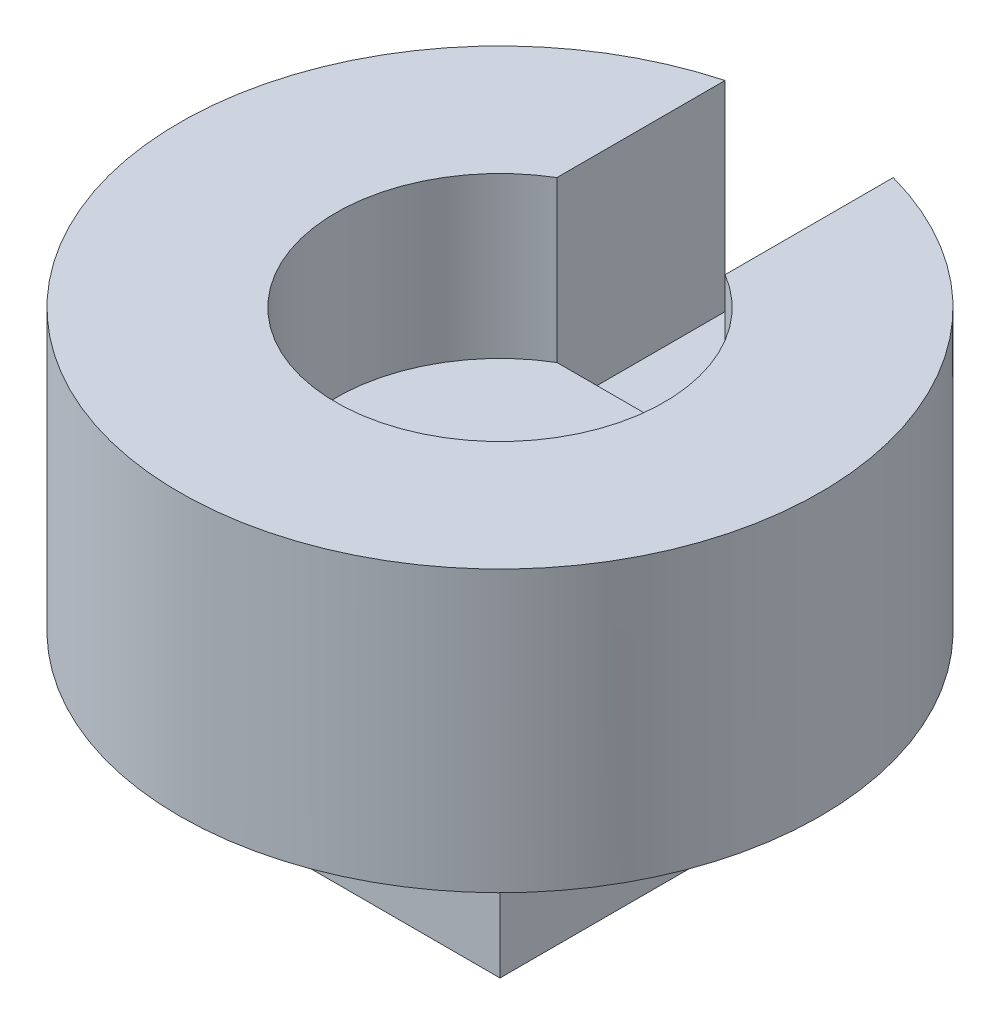
SolidWorks part; units mm, degrees
ref_plane "Front Plane" through (0, 0, 0) normal (0, 0, 1) x (1, 0, 0)
ref_plane "Top Plane" through (0, 0, 0) normal (0, 1, 0) x (1, 0, 0)
ref_plane "Right Plane" through (0, 0, 0) normal (1, 0, 0) x (0, 0, -1)
sketch "Sketch1" plane through (0, 0, 0) normal (0, 1, 0) x (1, 0, 0)
  line L1 (-1.25, -1.25) -> (1.25, -1.25)
  line L2 (-1.25, -1.25) -> (-1.25, 1.25)
  line L3 (-1.25, 1.25) -> (1.25, 1.25)
  line L4 (1.25, -1.25) -> (1.25, 1.25)
  line L5 (-1.25, -1.25) -> (1.25, 1.25) construction
  line L6 (-1.25, 1.25) -> (1.25, -1.25) construction
  point P0 (0, 0)
  dimension "D1" = 2.5
extrude "Boss-Extrude1" add sketch "Sketch1" along normal blind 2.5
sketch "Sketch2" plane through (0, 2.5, 0) normal (0, 1, 0) x (1, 0, 0)
  circle A0 centre (0, 0) radius 4
  dimension "D1" = 8
extrude "Boss-Extrude2" add sketch "Sketch2" along normal blind 3.5
sketch "Sketch3" plane through (0, 6, 0) normal (0, 1, 0) x (1, 0, 0)
  line L2 (-1.05, 1.7607) -> (1.05, 1.7607)
  line L3 (-1.05, 1.7607) -> (-1.05, 4)
  line L4 (-1.05, 4) -> (1.05, 4)
  line L5 (1.05, 1.7607) -> (1.05, 4)
  circle A0 centre (0, 0) radius 2.05
  circle A1 centre (0, 0) radius 4 construction
  circle M1 centre (0, 0) radius 4
  dimension "D1" = 4.1
  dimension "D2" = 2.1
extrude "Cut-Extrude1" cut sketch "Sketch3" against normal blind 2 contours L2 A0 | L2 A0 | A0 L5 L3 M1
sketch "Sketch5" plane through (0, 4, 0) normal (0, 1, 0) x (1, 0, 0)
  line L4 (-1.05, 1.7607) -> (1.05, 1.7607)
  line L5 (1.05, 1.7607) -> (1.05, 4)
  line L6 (1.05, 4) -> (-1.05, 4)
  line L7 (-1.05, 4) -> (-1.05, 1.7607)
  line L8 (-1.05, 1.7607) -> (1.05, 1.7607)
  line L9 (1.05, 1.7607) -> (1.05, 4)
  line L10 (1.05, 4) -> (-1.05, 4)
  line L11 (-1.05, 4) -> (-1.05, 1.7607)
  circle A1 centre (0, 0) radius 2.05
  circle A2 centre (0, 0) radius 2.05
  line M7 (1.05, 1.7607) -> (1.05, 3.8597)
  arc M8 (1.05, 3.8597) -> (-1.05, 3.8597) centre (0, 0) ccw
  line M9 (-1.05, 3.8597) -> (-1.05, 1.7607)
  dimension "D1" = 0
  dimension "D2" = 0
extrude "Cut-Extrude2" cut sketch "Sketch5" against normal blind 0.5 contours L8 A2 | A2 M7 M8 M9
equation "\"a\"= 1"
equation "\"b\"= 1"
equation "\"c\"= 1"
equation "\"d\"= 1"
equation "\"e\"= 1"
equation "\"x\"= 1"
equation "\"y\"= 1"
equation "\"z\"= 1"
